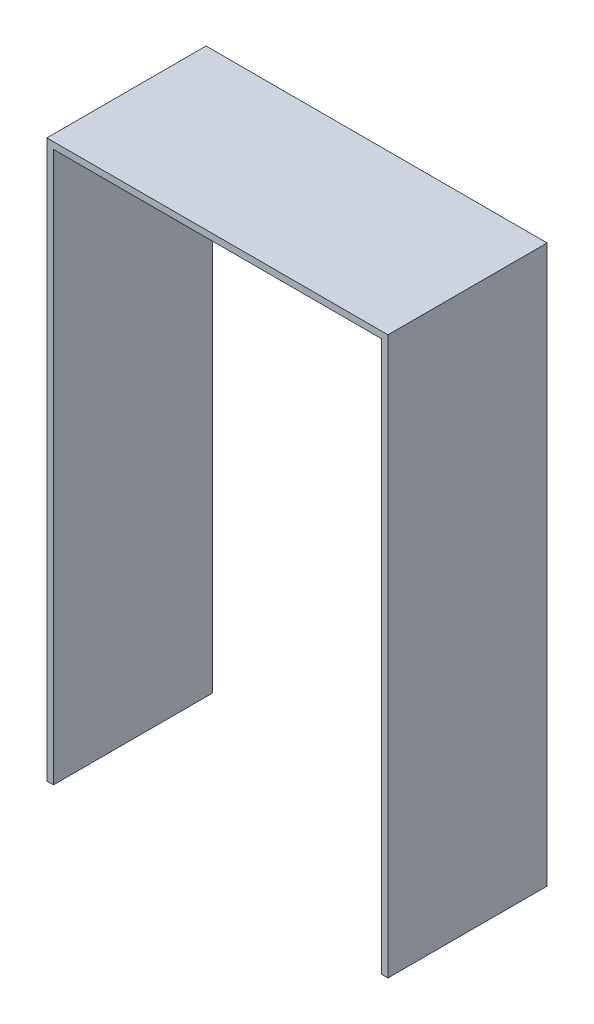
SolidWorks part; units mm, degrees
ref_plane "Front Plane" through (0, 0, 0) normal (0, 0, 1) x (1, 0, 0)
ref_plane "Top Plane" through (0, 0, 0) normal (0, 1, 0) x (1, 0, 0)
ref_plane "Right Plane" through (0, 0, 0) normal (1, 0, 0) x (0, 0, -1)
sketch "Sketch1" plane through (0, 0, 0) normal (0, 0, 1) x (1, 0, 0)
  line L5 (-81.661, 133.35) -> (81.661, 133.35)
  line L6 (-81.661, 133.35) -> (-81.661, -133.35)
  line L11 (-81.661, -133.35) -> (81.661, -133.35)
  line L12 (81.661, 133.35) -> (81.661, -133.35)
  line L13 (-81.661, 133.35) -> (81.661, -133.35) construction
  line L14 (-81.661, -133.35) -> (81.661, 133.35) construction
  point P0 (0, 0)
  dimension "D1" = 266.7
  dimension "D2" = 163.322
extrude "Boss-Extrude1" add sketch "Sketch1" along normal blind 76.2
sketch "Sketch2" plane through (0, 0, 76.2) normal (0, 0, 1) x (1, 0, 0)
  line L6 (-81.661, -133.35) -> (81.661, -133.35) construction
  line L7 (-78.486, -133.35) -> (78.486, -133.35)
  line L8 (-78.486, -133.35) -> (-78.486, 130.175)
  line L9 (-78.486, 130.175) -> (78.486, 130.175)
  line L10 (78.486, -133.35) -> (78.486, 130.175)
  line L11 (81.661, 133.35) -> (-81.661, 133.35) construction
  line L12 (-81.661, 133.35) -> (-81.661, -133.35) construction
  line L13 (81.661, -133.35) -> (81.661, 133.35) construction
  dimension "D1" = 3.175
  dimension "D2" = 3.175
  dimension "D3" = 3.175
extrude "Cut-Extrude1" cut sketch "Sketch2" against normal blind 76.2
